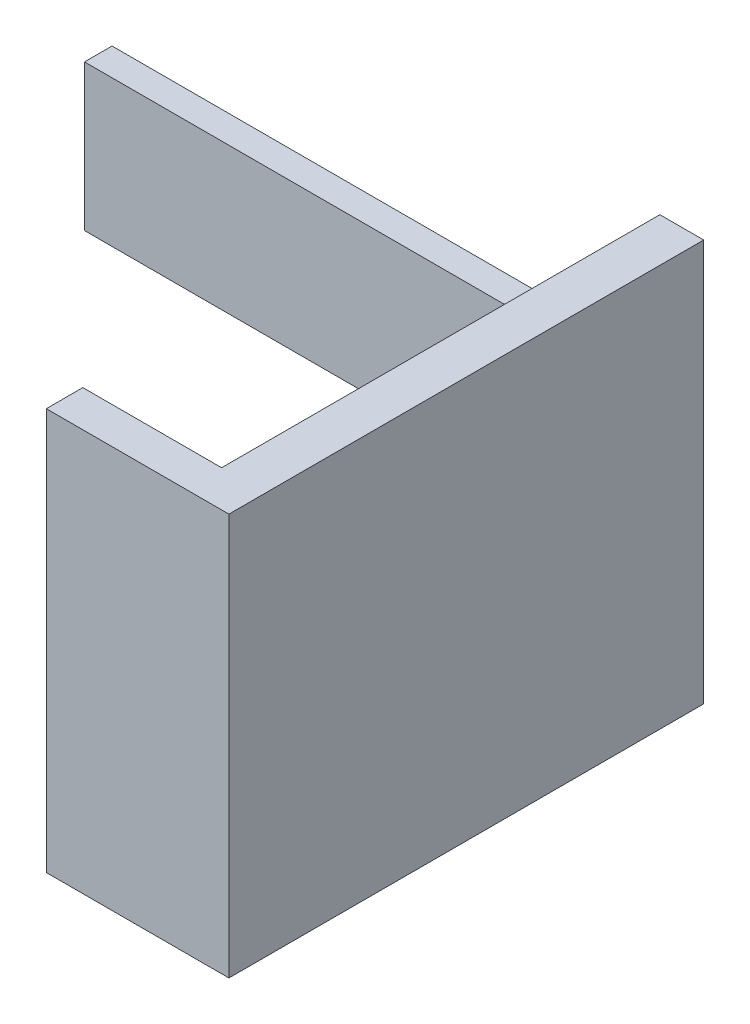
SolidWorks part; units mm, degrees
ref_plane "Front Plane" through (0, 0, 0) normal (0, 0, 1) x (1, 0, 0)
ref_plane "Top Plane" through (0, 0, 0) normal (0, 1, 0) x (1, 0, 0)
ref_plane "Right Plane" through (0, 0, 0) normal (1, 0, 0) x (0, 0, -1)
sketch "Sketch1" plane through (0, 0, 0) normal (0, 0, 1) x (1, 0, 0)
  line L1 (0, 0) -> (-50, 0)
  line L2 (0, 0) -> (0, 110)
  line L3 (0, 110) -> (-50, 110)
  line L4 (-50, 0) -> (-50, 110)
  dimension "D1" = 50
  dimension "D2" = 110
extrude "Boss-Extrude1" add sketch "Sketch1" along normal blind 10
sketch "Sketch2" plane through (0, 0, 0) normal (0, 0, -1) x (-1, 0, 0)
  line L0 (50, 0) -> (0, 0) construction
  line L1 (0, 110) -> (12, 110)
  line L2 (0, 110) -> (0, 0)
  line L3 (0, 0) -> (12, 0)
  line L4 (12, 110) -> (12, 0)
  dimension "D1" = 12
extrude "Boss-Extrude2" add sketch "Sketch2" along normal blind 120
sketch "Sketch3" plane through (-12, 0, 0) normal (-1, 0, 0) x (0, 0, 1)
  line L0 (-120, 0) -> (-120, 110) construction
  line L1 (-120, 75) -> (-112.4605, 75)
  line L2 (-120, 75) -> (-120, 35)
  line L3 (-120, 35) -> (-112.4605, 35)
  line L4 (-112.4605, 75) -> (-112.4605, 35)
  line L5 (-120, 0) -> (0, 0) construction
  dimension "D1" = 40
  dimension "D2" = 35
extrude "Boss-Extrude3" add sketch "Sketch3" along normal blind 150
